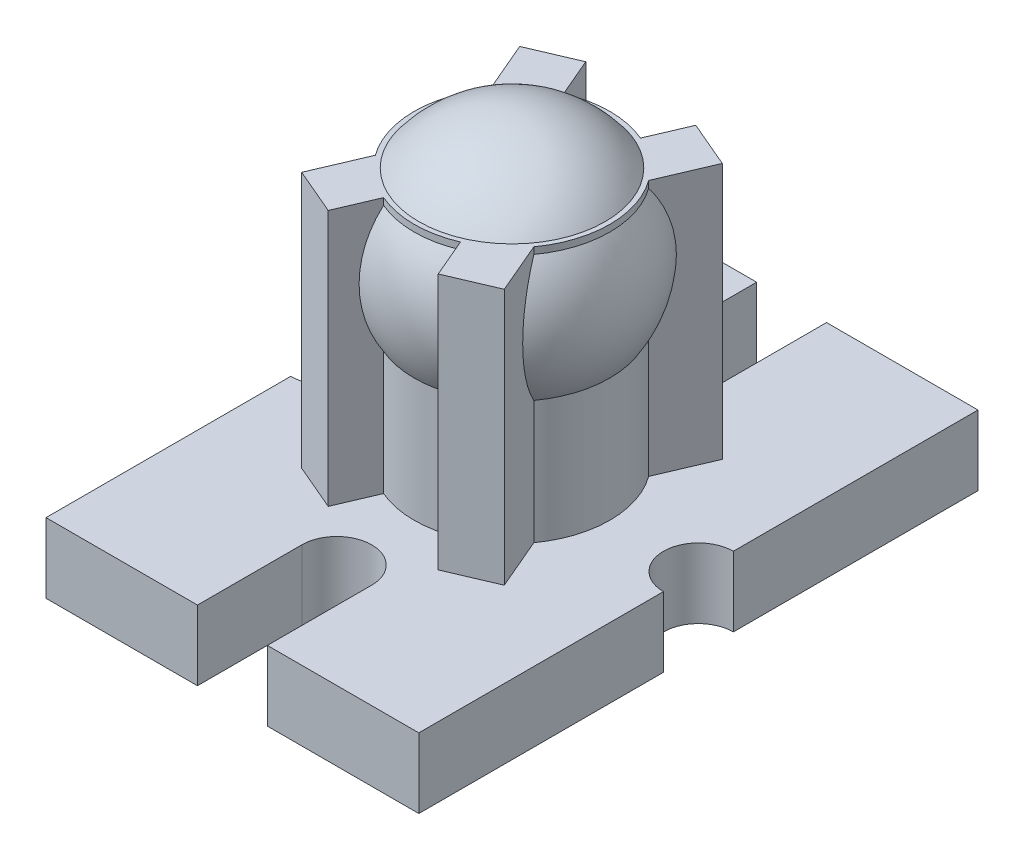
SolidWorks part; units mm, degrees
ref_plane "前视基准面" through (0, 0, 0) normal (0, 0, 1) x (1, 0, 0)
ref_plane "上视基准面" through (0, 0, 0) normal (0, 1, 0) x (1, 0, 0)
ref_plane "右视基准面" through (0, 0, 0) normal (1, 0, 0) x (0, 0, -1)
sketch "草图1" plane through (0, 0, 0) normal (0, 1, 0) x (1, 0, 0)
  line L0 (1.5, 12) -> (8, 12)
  line L1 (-8, 12) -> (-1.5, 12)
  line L2 (-8, 12) -> (-8, 1.5)
  line L3 (-8, -12) -> (-1.5, -12)
  line L4 (8, 12) -> (8, 1.5)
  line L5 (-8, 12) -> (8, -12) construction
  line L6 (-8, -12) -> (8, 12) construction
  line L7 (8, -1.5) -> (8, -12)
  line L8 (-8, -1.5) -> (-8, -12)
  line L9 (1.5, -12) -> (8, -12)
  line L10 (1.5, 12) -> (1.5, 7.52)
  line L11 (0, 0) -> (-16.3122, 0) construction
  line L12 (-1.5, 12) -> (-1.5, 7.52)
  line L13 (1.5, -7.52) -> (1.5, -12)
  line L14 (-1.5, -7.52) -> (-1.5, -12)
  arc A4 (8, 1.5) -> (8, -1.5) centre (8, 0) ccw
  arc A6 (-8, -1.5) -> (-8, 1.5) centre (-8, 0) ccw
  arc A8 (-1.5, 7.52) -> (1.5, 7.52) centre (0, 7.52) ccw
  arc A9 (-1.5, -7.52) -> (1.5, -7.52) centre (0, -7.52) cw
  point P0 (0, 0)
  dimension "D3" = 3
  dimension "D4" = 7.52
  dimension "D5" = 3
  dimension "D6" = 3
  dimension "D1" = 16
  dimension "D2" = 24
extrude "凸台-拉伸1" add sketch "草图1" along normal blind 3
sketch "草图2" plane through (0, 0, 0) normal (1, 0, 0) x (0, 0, -1)
  line L0 (0, 3) -> (0, 45.2703) construction
  line L1 (1.5, 3) -> (-1.5, 3) construction
  line L2 (0, 16) -> (0, 6)
  line L3 (1.5, 0) -> (12, 0) construction
  arc A0 (0, 6) -> (0, 16) centre (0, 11) ccw
  dimension "D1" = 10
  dimension "D2" = 16
revolve "旋转1" add sketch "草图2" angle 360 about L0
sketch "草图3" plane through (0, 3, 0) normal (0, 1, 0) x (1, 0, 0)
  line L0 (-9.516, 0) -> (9.46, 0) construction
  line L1 (0, 0) -> (0, 14.6945) construction
  line L36 (-23.3765, 17.6868) -> (-23.3765, -9.3132) construction
  line L37 (-13.8765, 4.1868) -> (-32.8765, 4.1868) construction
  line L38 (-21.4128, 8.785) -> (-21.076, 9.5493)
  line L39 (-19.0978, -0.3041) -> (-19.6217, 0.885)
  line L40 (-21.4128, 8.785) -> (-21.796, 7.8876)
  line L41 (-19.6217, 7.4885) -> (-20.0675, 6.4768)
  line L42 (-19.6217, 0.885) -> (-20.0675, 1.8967)
  line L43 (-21.4128, -0.4115) -> (-21.796, 0.486)
  line L44 (-21.076, 9.5493) -> (-19.0978, 8.6777)
  line L45 (-19.0978, 8.6777) -> (-19.6217, 7.4885)
  line L46 (-19.0978, -0.3041) -> (-21.09, -1.1819)
  line L47 (-21.09, -1.1819) -> (-21.4128, -0.4115)
  line L48 (-27.1313, 0.885) -> (-26.6855, 1.8967)
  line L49 (-25.6631, -1.1819) -> (-25.3403, -0.4115)
  line L50 (-27.6552, -0.3041) -> (-25.6631, -1.1819)
  line L51 (-25.3403, -0.4115) -> (-24.957, 0.486)
  line L52 (-27.6552, -0.3041) -> (-27.1313, 0.885)
  line L53 (-27.6552, 8.6777) -> (-27.1313, 7.4885)
  line L54 (-25.677, 9.5493) -> (-27.6552, 8.6777)
  line L55 (-27.1313, 7.4885) -> (-26.6855, 6.4768)
  line L56 (-25.3403, 8.785) -> (-24.957, 7.8876)
  line L57 (-25.3403, 8.785) -> (-25.677, 9.5493)
  line L58 (1.6498, 3.8624) -> (2.3608, 5.5269)
  line L59 (2.3608, 5.5269) -> (4.3472, 4.6784)
  line L60 (4.3472, 4.6784) -> (3.4013, 2.464)
  line L61 (-1.6498, 3.8624) -> (-2.3608, 5.5269)
  line L62 (-2.3608, 5.5269) -> (-4.3472, 4.6784)
  line L63 (-4.3472, 4.6784) -> (-3.4013, 2.464)
  line L64 (4.3472, -4.6784) -> (3.4013, -2.464)
  line L65 (1.6498, -3.8624) -> (2.3608, -5.5269)
  line L66 (2.3608, -5.5269) -> (4.3472, -4.6784)
  line L67 (-1.6498, -3.8624) -> (-2.3608, -5.5269)
  line L68 (-4.3472, -4.6784) -> (-3.4013, -2.464)
  line L69 (-2.3608, -5.5269) -> (-4.3472, -4.6784)
  arc A4 (-26.6855, 6.4768) -> (-26.6855, 1.8967) centre (-23.3765, 4.1868) ccw
  arc A10 (-21.796, 7.8876) -> (-24.957, 7.8876) centre (-23.3765, 4.1868) ccw
  arc A11 (-20.0675, 1.8967) -> (-20.0675, 6.4768) centre (-23.3765, 4.1868) ccw
  arc A12 (-24.957, 0.486) -> (-21.796, 0.486) centre (-23.3765, 4.1868) ccw
  arc A13 (-3.4013, 2.464) -> (-3.4013, -2.464) centre (0, 0) ccw
  arc A14 (1.6498, 3.8624) -> (-1.6498, 3.8624) centre (0, 0) ccw
  arc A15 (3.4013, -2.464) -> (3.4013, 2.464) centre (0, 0) ccw
  arc A16 (-1.6498, -3.8624) -> (1.6498, -3.8624) centre (0, 0) ccw
  dimension "D3" = 23.13
  dimension "D8" = 4.0242
  dimension "D2" = 8.4
  dimension "D4" = 1.81
  dimension "D5" = 2.16
  dimension "D6" = 2.1617
  dimension "D7" = 23.126
  dimension "D9" = 2.405
  dimension "D10" = 1.811
extrude "凸台-拉伸2" add sketch "草图3" along normal blind 11
